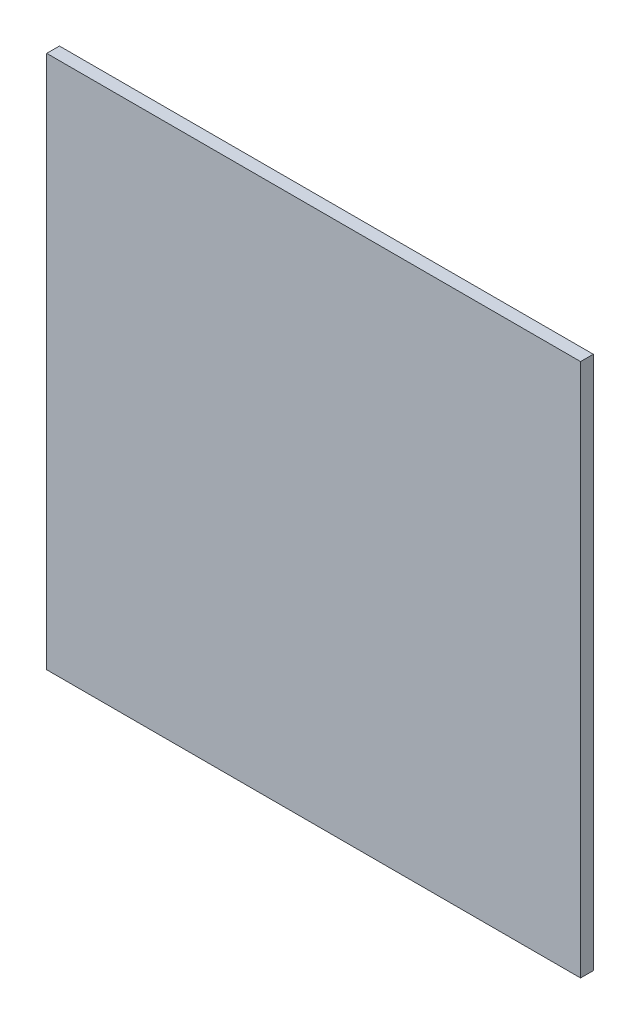
SolidWorks part; units mm, degrees
ref_plane "Front Plane" through (0, 0, 0) normal (0, 0, 1) x (1, 0, 0)
ref_plane "Top Plane" through (0, 0, 0) normal (0, 1, 0) x (1, 0, 0)
ref_plane "Right Plane" through (0, 0, 0) normal (1, 0, 0) x (0, 0, -1)
sketch "Sketch1" plane through (0, 0, 0) normal (0, 0, 1) x (1, 0, 0)
  line L0 (0, 4.7625) -> (0, 0) construction
  line L1 (-200, 4.7625) -> (0, 4.7625)
  line L2 (-200, 4.7625) -> (-200, 204.7625)
  line L3 (-200, 204.7625) -> (0, 204.7625)
  line L4 (0, 4.7625) -> (0, 204.7625)
  dimension "D1" = 200
extrude "Boss-Extrude1" add sketch "Sketch1" against normal blind 4.7625 contours L2 L3 L4 L1
